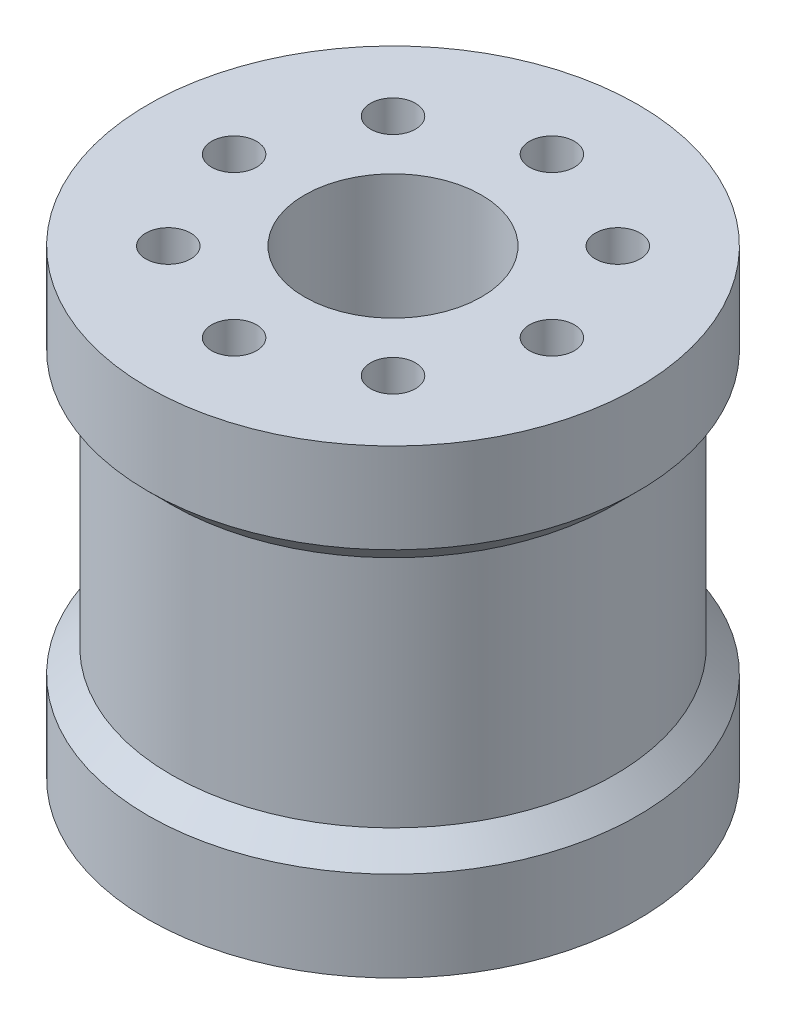
SolidWorks part; units mm, degrees
ref_plane "Front Plane" through (0, 0, 0) normal (0, 0, 1) x (1, 0, 0)
ref_plane "Top Plane" through (0, 0, 0) normal (0, 1, 0) x (1, 0, 0)
ref_plane "Right Plane" through (0, 0, 0) normal (1, 0, 0) x (0, 0, -1)
sketch "Sketch1" plane through (0, 0, 0) normal (0, 0, 1) x (1, 0, 0)
  line L0 (0, 0) -> (0, 20.5) construction
  line L1 (-3, 0) -> (-3, 20.5)
  line L2 (-3, 0) -> (-10.9, 0)
  line L3 (-10.9, 0) -> (-10.9, 4)
  line L4 (-10.9, 4) -> (-9.855, 5.045)
  line L5 (-9.855, 15.455) -> (-9.855, 5.045)
  line L6 (-9.855, 15.455) -> (-10.9, 16.5)
  line L7 (-10.9, 16.5) -> (-10.9, 20.5)
  line L8 (-10.9, 20.5) -> (-3, 20.5)
  line L9 (-3, 0) -> (0, 0) construction
  line L10 (-3, 20.5) -> (0, 20.5) construction
  line L11 (-10.9, 16.5) -> (-10.9, 4) construction
  point P10 (-6.95, 0)
  dimension "D1" = 10.9
  dimension "D2" = 9.855
  dimension "D3" = 20.5
  dimension "D4" = 4
  dimension "D5" = 4
  dimension "D6" = 45
  dimension "D7" = 45
  dimension "D8" = 3
revolve "Revolve1" add sketch "Sketch1" angle 360 about L0
sketch "Sketch2" plane through (0, 20.5, 0) normal (0, 1, 0) x (1, 0, 0)
  line L0 (0, 10.116) -> (0, 0) construction
  line L1 (5, -5) -> (-5, -5) construction
  line L2 (5, -5) -> (5, 5) construction
  line L3 (5, 5) -> (-5, 5) construction
  line L4 (-5, -5) -> (-5, 5) construction
  line L5 (5, -5) -> (-5, 5) construction
  line L6 (5, 5) -> (-5, -5) construction
  line L7 (7.0711, 0) -> (0, 7.0711) construction
  line L8 (7.0711, 0) -> (0, -7.0711) construction
  line L9 (0, 7.0711) -> (-7.0711, 0) construction
  line L10 (0, -7.0711) -> (-7.0711, 0) construction
  line L11 (7.0711, 0) -> (-7.0711, 0) construction
  line L12 (0, 7.0711) -> (0, -7.0711) construction
  circle A0 centre (0, 0) radius 3.935
  circle A1 centre (-5, 5) radius 1
  circle A2 centre (5, 5) radius 1
  circle A3 centre (5, -5) radius 1
  circle A4 centre (-5, -5) radius 1
  circle A5 centre (-7.0711, 0) radius 1
  circle A6 centre (0, 7.0711) radius 1
  circle A7 centre (7.0711, 0) radius 1
  circle A8 centre (0, -7.0711) radius 1
  dimension "D1" = 7.87
  dimension "D3" = 2
  dimension "D2" = 45
  dimension "D4" = 10
  dimension "D5" = 45
  dimension "D6" = 10
extrude "Cut-Extrude1" cut sketch "Sketch2" against normal blind 45
